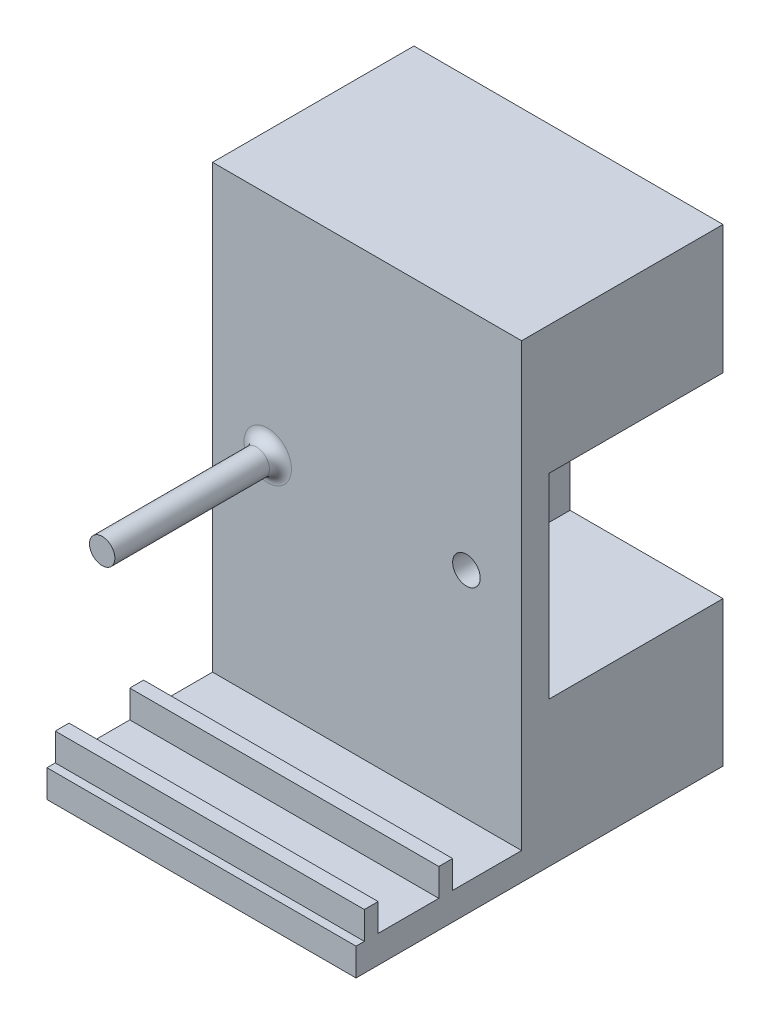
SolidWorks part; units mm, degrees
ref_plane "Front Plane" through (0, 0, 0) normal (0, 0, 1) x (1, 0, 0)
ref_plane "Top Plane" through (0, 0, 0) normal (0, 1, 0) x (1, 0, 0)
ref_plane "Right Plane" through (0, 0, 0) normal (1, 0, 0) x (0, 0, -1)
sketch "Sketch1" plane through (0, 0, 0) normal (0, 0, 1) x (1, 0, 0)
  line L1 (-35.56, 50.8) -> (35.56, 50.8)
  line L2 (-35.56, 50.8) -> (-35.56, -50.8)
  line L3 (-35.56, -50.8) -> (35.56, -50.8)
  line L4 (35.56, 50.8) -> (35.56, -50.8)
  line L5 (-35.56, 50.8) -> (35.56, -50.8) construction
  line L6 (-35.56, -50.8) -> (35.56, 50.8) construction
  point P0 (0, 0)
  dimension "D1" = 71.12
  dimension "D2" = 101.6
extrude "Boss-Extrude1" add sketch "Sketch1" along normal blind 6.35 contours L4 L3 L2 L1
sketch "Sketch2" plane through (0, 0, 6.35) normal (0, 0, 1) x (1, 0, 0)
  line L0 (-35.56, -50.8) -> (35.56, -50.8) construction
  line L2 (35.56, 50.8) -> (35.56, -50.8) construction
  circle A0 centre (22.86, -1.27) radius 3.175
  dimension "D1" = 6.35
  dimension "D2" = 49.53
  dimension "D3" = 12.7
extrude "Cut-Extrude2" cut sketch "Sketch2" against normal blind 6.35 contours A0
sketch "Sketch4" plane through (0, 0, 6.35) normal (0, 0, 1) x (1, 0, 0)
  line L0 (-35.56, -50.8) -> (35.56, -50.8) construction
  circle A0 centre (-22.86, -1.27) radius 2.921
  circle A1 centre (22.86, -1.27) radius 3.175 construction
  circle A2 centre (-68.58, -1.27) radius 3.175
  circle A3 centre (-114.3, -1.27) radius 3.175
  dimension "D1" = 5.842
  dimension "D3" = 6.35
  dimension "D9" = 6.35
  dimension "D2" = 45.72
  dimension "D4" = 45.72
  dimension "D5" = 45.72
  dimension "D6" = 49.53
  dimension "D7" = 49.53
  dimension "D8" = 49.53
sketch "Sketch5" plane through (0, 0, 6.35) normal (0, 0, 1) x (1, 0, 0)
  line L1 (-35.56, -50.8) -> (35.56, -50.8)
  line L2 (-35.56, -50.8) -> (-35.56, -57.15)
  line L3 (-35.56, -57.15) -> (35.56, -57.15)
  line L4 (35.56, -50.8) -> (35.56, -57.15)
  dimension "D1" = 71.12
sketch "Sketch6" plane through (0, 0, 0) normal (0, 0, -1) x (-1, 0, 0)
  line L0 (-35.56, 21.23) -> (-35.56, 50.8)
  line L1 (-45.36, 21.23) -> (-0.36, 21.23)
  line L2 (-45.36, 21.23) -> (-45.36, -23.77)
  line L3 (-45.36, -23.77) -> (-0.36, -23.77)
  line L4 (-0.36, 21.23) -> (-0.36, -23.77)
  line L5 (-45.36, 21.23) -> (-0.36, -23.77) construction
  line L6 (-45.36, -23.77) -> (-0.36, 21.23) construction
  line L7 (-35.56, 50.8) -> (-35.56, -50.8) construction
  line L8 (35.56, 50.8) -> (-35.56, 50.8) construction
  line L9 (-35.56, 50.8) -> (35.56, 50.8)
  line L10 (35.56, 50.8) -> (35.56, -50.8)
  line L11 (35.56, -50.8) -> (-35.56, -50.8)
  line L12 (-35.56, -50.8) -> (-35.56, -23.77)
  point P0 (-22.86, -1.27)
  line M6 (35.56, 50.8) -> (-35.56, 50.8)
  line M7 (-35.56, 50.8) -> (-35.56, -50.8)
  line M8 (-35.56, -50.8) -> (35.56, -50.8)
  line M9 (35.56, -50.8) -> (35.56, 50.8)
  dimension "D1" = 45
  dimension "D2" = 45
extrude "Boss-Extrude2" add sketch "Sketch6" along normal blind 40 contours L1 L4 L3 M7 M8 M9 M6
extrude "Boss-Extrude4" add sketch "Sketch4" along normal blind 38.1 contours A0
fillet "Fillet1" radius 2.54 1 edges at (-25.781, -1.27, 6.35)
extrude "Boss-Extrude5" add sketch "Sketch5" along normal blind 38.1 and the other way through all contours L3 L4 L1 L2
sketch "Sketch8" plane through (0, -50.8, 0) normal (0, 1, 0) x (1, 0, 0)
  line L0 (-35.56, -6.35) -> (-35.56, -44.45) construction
  line L1 (-35.56, -22.225) -> (35.56, -22.225)
  line L2 (-35.56, -22.225) -> (-35.56, -25.4)
  line L3 (-35.56, -25.4) -> (35.56, -25.4)
  line L4 (35.56, -22.225) -> (35.56, -25.4)
  line L5 (35.56, -6.35) -> (35.56, -44.45) construction
  line L7 (-35.56, -39.37) -> (35.56, -39.37)
  line L8 (-35.56, -39.37) -> (-35.56, -42.545)
  line L9 (-35.56, -42.545) -> (35.56, -42.545)
  line L10 (35.56, -39.37) -> (35.56, -42.545)
  line L11 (-35.56, -6.35) -> (35.56, -6.35) construction
  dimension "D1" = 3.175
  dimension "D2" = 19.05
  dimension "D3" = 0
  dimension "D4" = 13.97
extrude "Boss-Extrude6" add sketch "Sketch8" along normal blind 6.35
